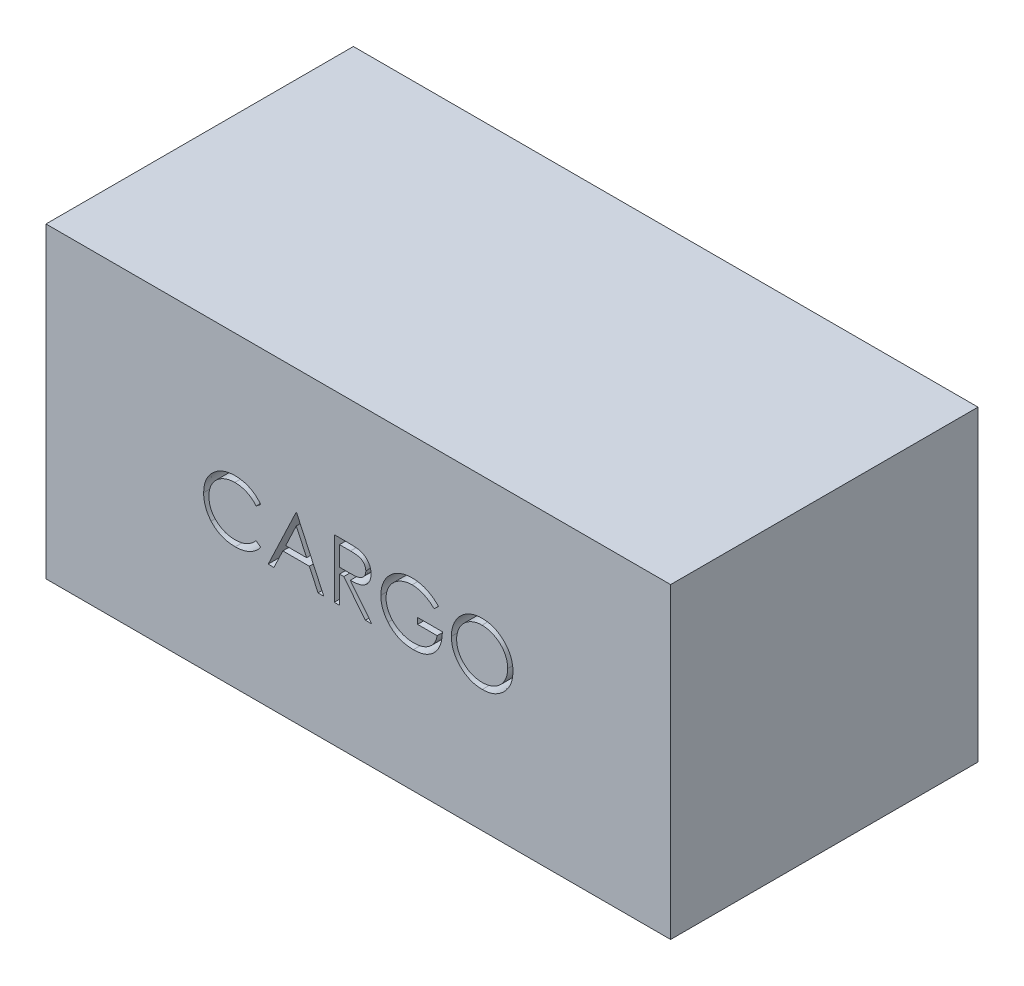
SolidWorks part; units mm, degrees
ref_plane "Front Plane" through (0, 0, 0) normal (0, 0, 1) x (1, 0, 0)
ref_plane "Top Plane" through (0, 0, 0) normal (0, 1, 0) x (1, 0, 0)
ref_plane "Right Plane" through (0, 0, 0) normal (1, 0, 0) x (0, 0, -1)
sketch "Sketch1" plane through (0, 0, 0) normal (0, 1, 0) x (1, 0, 0)
  line L1 (-69.0476, 30.7823) -> (134.1524, 30.7823)
  line L2 (-69.0476, 30.7823) -> (-69.0476, -69.2177)
  line L3 (-69.0476, -69.2177) -> (134.1524, -69.2177)
  line L4 (134.1524, 30.7823) -> (134.1524, -69.2177)
  dimension "D1" = 100
  dimension "D2" = 203.2
extrude "Boss-Extrude1" add sketch "Sketch1" along normal blind 100
sketch "Sketch2" plane through (0, 0, 69.2177) normal (0, 0, 1) x (1, 0, 0)
  text T0 "CARGO" font "Century Gothic" height in points 72
extrude "Cut-Extrude1" cut sketch "Sketch2" against normal blind 10
